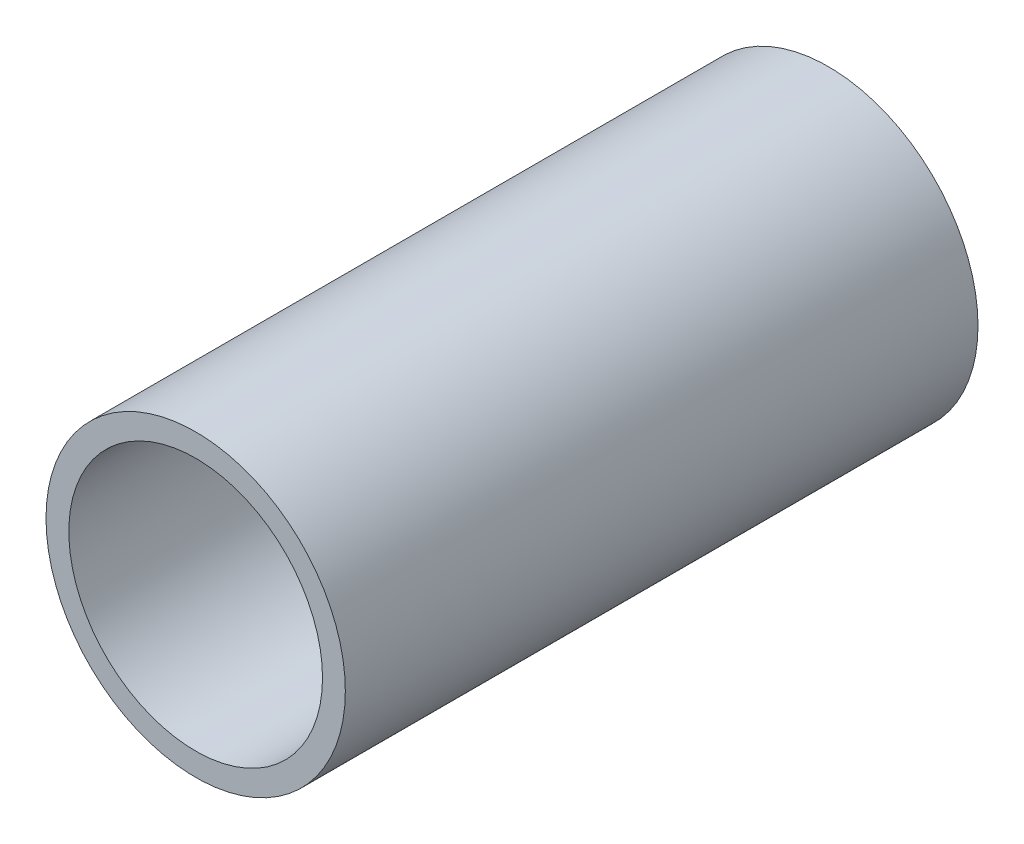
SolidWorks part; units mm, degrees
material "AISI 1020"
ref_plane "Plano frontal" through (0, 0, 0) normal (0, 0, 1) x (1, 0, 0)
ref_plane "Plano superior" through (0, 0, 0) normal (0, 1, 0) x (1, 0, 0)
ref_plane "Plano direito" through (0, 0, 0) normal (1, 0, 0) x (0, 0, -1)
sketch "Esboço1" plane through (0, 0, 0) normal (0, 0, 1) x (1, 0, 0)
  circle A0 centre (0, 0) radius 24.13
  circle A1 centre (0, 0) radius 20.45
  dimension "D1" = 48.26
  dimension "D2" = 40.9
extrude "Extrusão1" add sketch "Esboço1" along normal mid plane 102
sketch "Croquis1" plane through (0, 0, 0) normal (0, 0, 1) x (1, 0, 0)
  circle A0 centre (0, 0) radius 27.1628
